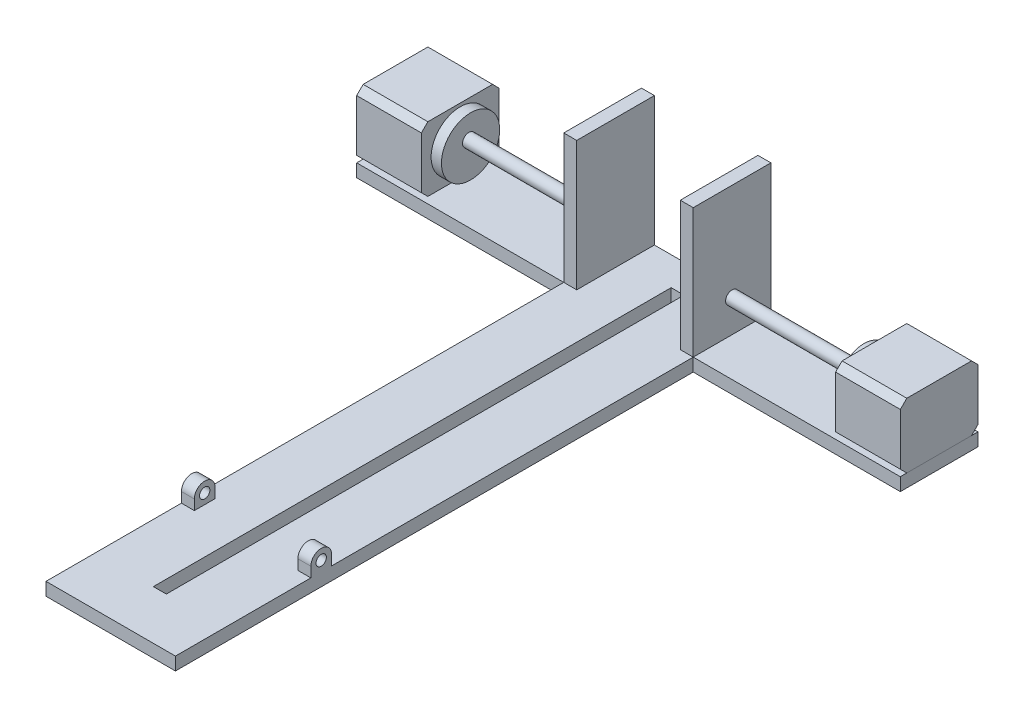
SolidWorks part; units mm, degrees
ref_plane "前视基准面" through (0, 0, 0) normal (0, 0, 1) x (1, 0, 0)
ref_plane "上视基准面" through (0, 0, 0) normal (0, 1, 0) x (1, 0, 0)
ref_plane "右视基准面" through (0, 0, 0) normal (1, 0, 0) x (0, 0, -1)
sketch "草图1" plane through (0, 0, 0) normal (0, 0, 1) x (1, 0, 0)
  line L1 (-50, -5) -> (50, -5)
  line L2 (-50, -5) -> (-50, 5)
  line L3 (-50, 5) -> (50, 5)
  line L4 (50, -5) -> (50, 5)
  line L5 (-50, -5) -> (50, 5) construction
  line L6 (-50, 5) -> (50, -5) construction
  point P0 (0, 0)
extrude "凸台-拉伸1" add sketch "草图1" along normal blind 460
sketch "草图2" plane through (0, 5, 0) normal (0, 1, 0) x (1, 0, 0)
  line L1 (-5, -422.0499) -> (5, -422.0499)
  line L2 (-5, -422.0499) -> (-5, -22.0499)
  line L3 (-5, -22.0499) -> (5, -22.0499)
  line L4 (5, -422.0499) -> (5, -22.0499)
  line L5 (-5, -422.0499) -> (5, -22.0499) construction
  line L6 (-5, -22.0499) -> (5, -422.0499) construction
  point P0 (0, -222.0499)
extrude "切除-拉伸1" cut sketch "草图2" against normal blind 460
sketch "草图3" plane through (0, 5, 0) normal (0, 1, 0) x (1, 0, 0)
  line L0 (-38.8737, -347.4839) -> (39.5285, -347.4839)
  dimension "D1" = 78.4023
sketch "草图4" plane through (-50, 0, 0) normal (-1, 0, 0) x (0, 0, 1)
  line L0 (339.3969, 12.7987) -> (339.3969, 5)
  line L1 (460, 5) -> (0, 5) construction
  line L2 (346.5208, 5) -> (355.3969, 5)
  line L3 (355.3969, 5) -> (355.3969, 12.7987)
  circle A0 centre (347.3969, 12.7987) radius 4
  arc A2 (355.3969, 12.7987) -> (339.3969, 12.7987) centre (347.3969, 12.7987) ccw
  line M4 (460, 5) -> (0, 5)
  dimension "D1" = 7.7987
  dimension "D2" = 16
  dimension "D3" = 7.7987
extrude "凸台-拉伸2" add sketch "草图4" against normal blind 10 contours L3 A2 L0 A0 M4
mirror "镜向1" about plane through (0, 0, 0) normal (1, 0, 0) of "凸台-拉伸2"
sketch "草图5" plane through (0, -5, 0) normal (0, -1, 0) x (1, 0, 0)
  line L1 (-50, 0) -> (-40, 0)
  line L2 (-50, 0) -> (-50, 60)
  line L3 (-50, 60) -> (-40, 60)
  line L4 (-40, 0) -> (-40, 60)
  line L5 (50, 0) -> (40, 0)
  line L6 (50, 0) -> (50, 60)
  line L7 (50, 60) -> (40, 60)
  line L8 (40, 0) -> (40, 60)
  dimension "D1" = 10
  dimension "D2" = 60
  dimension "D3" = 10
  dimension "D4" = 60
extrude "凸台-拉伸3" add sketch "草图5" against normal blind 100 from offset 10 separate body offset against normal yes
sketch "草图6" plane through (0, 5, 0) normal (0, 1, 0) x (1, 0, 0)
  line L1 (50, 0) -> (210, 0)
  line L2 (50, 0) -> (50, -60)
  line L3 (50, -60) -> (210, -60)
  line L4 (210, 0) -> (210, -60)
  line L5 (-50, 0) -> (-210, 0)
  line L6 (-50, 0) -> (-50, -60)
  line L7 (-50, -60) -> (-210, -60)
  line L8 (-210, 0) -> (-210, -60)
  dimension "D1" = 160
  dimension "D2" = 60
  dimension "D3" = 160
  dimension "D4" = 60
extrude "凸台-拉伸4" add sketch "草图6" against normal blind 10
sketch "草图7" plane through (0, 5, 0) normal (0, 1, 0) x (1, 0, 0)
  line L0 (-210, -60) -> (-50, -60) construction
  line L1 (-210, 0) -> (-160, 0)
  line L2 (-210, 0) -> (-210, -60)
  line L3 (-210, -60) -> (-160, -60)
  line L4 (-160, 0) -> (-160, -60)
  line L5 (50, -60) -> (210, -60) construction
  line L6 (210, 0) -> (160, 0)
  line L7 (210, 0) -> (210, -60)
  line L8 (210, -60) -> (160, -60)
  line L9 (160, 0) -> (160, -60)
  dimension "D1" = 50
  dimension "D2" = 50
extrude "凸台-拉伸5" add sketch "草图7" along normal blind 50 separate body
chamfer "倒角1" distance 5 angle 45 4 edges at (-185, 5, 60) (-185, 5, 0) (-185, 55, 60) (-185, 55, 0)
chamfer "倒角2" distance 5 angle 45 4 edges at (185, 5, 60) (185, 55, 60) (185, 5, 0) (185, 55, 0)
sketch "草图8" plane through (160, 0, 0) normal (-1, 0, 0) x (0, 0, 1)
  line L0 (30, 55) -> (30, 5) construction
  line L1 (5, 55) -> (55, 55) construction
  line L2 (5, 5) -> (55, 5) construction
  circle A0 centre (30, 30) radius 20.1215
extrude "凸台-拉伸6" add sketch "草图8" along normal blind 8 separate body contours A0
sketch "草图9" plane through (-160, 0, 0) normal (1, 0, 0) x (0, 0, -1)
  line L0 (-30, 55) -> (-30, 5) construction
  line L1 (-55, 55) -> (-5, 55) construction
  line L2 (-55, 5) -> (-5, 5) construction
  circle A0 centre (-30, 30) radius 22.5
  dimension "D1" = 45
extrude "凸台-拉伸7" add sketch "草图9" along normal blind 8 separate body
sketch "草图10" plane through (152, 0, 0) normal (-1, 0, 0) x (0, 0, 1)
  circle A0 centre (30, 30) radius 5
  dimension "D1" = 10
extrude "凸台-拉伸8" add sketch "草图10" along normal blind 102 separate body
sketch "草图11" plane through (-152, 0, 0) normal (1, 0, 0) x (0, 0, -1)
  circle A0 centre (-31.2417, 35) radius 5
  dimension "D1" = 10
extrude "凸台-拉伸9" add sketch "草图11" along normal blind 108
